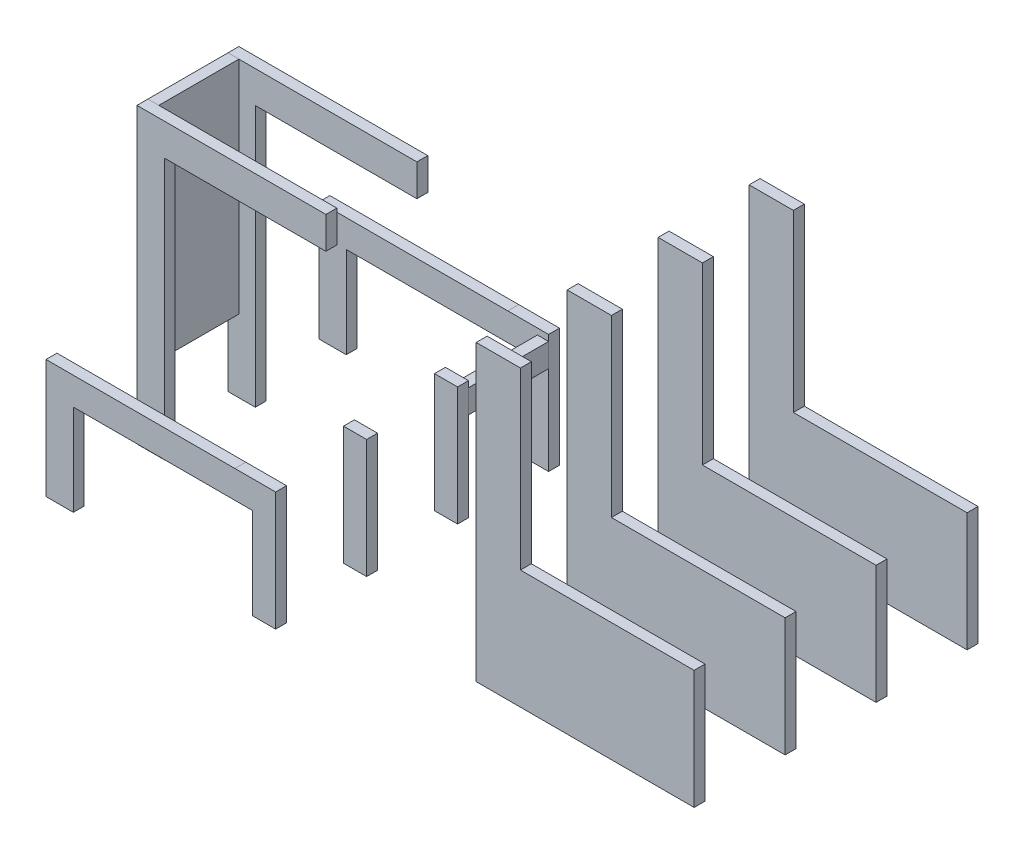
SolidWorks part; units mm, degrees
material "AISI 316 Stainless Steel Sheet (SS)"
ref_plane "Front Plane" through (0, 0, 0) normal (0, 0, 1) x (1, 0, 0)
ref_plane "Top Plane" through (0, 0, 0) normal (0, 1, 0) x (1, 0, 0)
ref_plane "Right Plane" through (0, 0, 0) normal (1, 0, 0) x (0, 0, -1)
sketch "Sketch1"
  dimension "D1" = 50
  dimension "D2" = 123.013
  dimension "D3" = 173.013
  dimension "D4" = 229.7747
  dimension "D5" = 171.9467
  dimension "D6" = 93.5182
  dimension "D7" = 166.8435
  dimension "D8" = 228.8836
  dimension "D9" = 229.7747
  dimension "D10" = 744.7238
  dimension "D11" = 447.3982
  dimension "D12" = 748.8136
  dimension "D13" = 598.8136
  dimension "D14" = 130
  dimension "D15" = 130
sketch_block_instance "Block1-1"
sketch_block "Block1" parameters "D1"=100, "D2"=20
sketch_block_instance "Block1-2"
sketch_block_instance "Block2-1"
sketch_block "Block2" parameters "D1"=50
sketch_block_instance "Block3-1"
sketch_block "Block3" parameters "D1"=150, "D2"=20
sketch_block_instance "Block3-2"
sketch_block_instance "Block4-1"
sketch_block "Block4" parameters "D2"=2.213, "D1"=50
sketch_block_instance "Block1-4"
sketch_block_instance "Block3-4"
sketch_block_instance "Block1-5"
sketch_block_instance "Block4-2"
sketch_block_instance "Block4-4"
sketch_block_instance "Block5-1"
sketch_block "Block5" parameters "D1"=200, "D2"=75, "D3"=75, "D4"=100
sketch_block_instance "Block5-2"
sketch_block_instance "Block2-2"
sketch_block_instance "Block3-8"
sketch "Sketch2" plane through (0, 0, 0) normal (0, 0, 1) x (1, 0, 0)
  line L0 (-466.6958, -172.0881) -> (-466.6958, -15.3598)
  line L1 (-244.3322, -302.6343) -> (-496.7215, -302.6343)
  line L2 (-244.3322, -302.6343) -> (-244.3322, -172.0881)
  line L3 (-244.3322, -172.0881) -> (-466.6958, -172.0881)
  line L4 (-496.7215, -302.6343) -> (-496.7215, 19.7481)
  line L5 (-466.6958, -15.3598) -> (-289.0913, -15.3598)
  line L6 (-289.0913, -15.3598) -> (-289.0913, 19.7481)
  line L7 (-289.0913, 19.7481) -> (-496.7215, 19.7481)
  line L8 (24.7298, -111.854) -> (215.6434, -111.854)
  line L9 (215.6434, -111.854) -> (215.6434, -242.4002)
  line L10 (215.6434, -242.4002) -> (-23.9267, -242.4002)
  line L11 (-23.9267, -242.4002) -> (-23.9267, 80.4875)
  line L12 (-23.9267, 80.4875) -> (24.7298, 80.4875)
  line L13 (24.7298, 80.4875) -> (24.7298, -111.854)
extrude "Boss-Extrude1" add sketch "Sketch2" along normal blind 12
pattern_linear "LPattern1" count 4 spacing 100 along (0, 0, 1) of bodies 102 101
sketch "Sketch3" plane through (0, 0, 112) normal (0, 0, 1) x (1, 0, 0)
  line L0 (-496.7215, -302.6343) -> (-244.3322, -302.6343) construction
  line L1 (-466.6958, -302.6343) -> (-269.725, -302.6343)
  line L2 (-466.6958, -302.6343) -> (-466.6958, -202.4226)
  line L3 (-466.6958, -202.4226) -> (-269.725, -202.4226)
  line L4 (-269.725, -302.6343) -> (-269.725, -202.4226)
  line L5 (-466.6958, -172.0881) -> (-466.6958, -15.3598) construction
  line L6 (-244.3322, -302.6343) -> (-244.3322, -172.0881) construction
  dimension "D1" = 25.3928
extrude "Cut-Extrude1" cut sketch "Sketch3" against normal through all both and the other way through all
sketch "Sketch4" plane through (-496.7215, 0, 0) normal (-1, 0, 0) x (0, 0, 1)
  line L25 (200, 19.7481) -> (200, -302.6343) construction
  line L26 (112, 19.7481) -> (200, 19.7481)
  line L27 (112, 19.7481) -> (112, -222.937)
  line L28 (112, -222.937) -> (200, -222.937)
  line L29 (200, 19.7481) -> (200, -222.937)
extrude "Boss-Extrude2" add sketch "Sketch4" against normal blind 12 separate body
sketch "Sketch5" plane through (0, 0, 12) normal (0, 0, 1) x (1, 0, 0)
  line L0 (-244.3322, -302.6343) -> (-244.3322, -172.0881) construction
  line L1 (-244.3322, -178.8069) -> (-256.5963, -178.8069)
  line L2 (-244.3322, -178.8069) -> (-244.3322, -204.6688)
  line L3 (-244.3322, -204.6688) -> (-256.5963, -204.6688)
  line L4 (-256.5963, -178.8069) -> (-256.5963, -204.6688)
extrude "Boss-Extrude3" add sketch "Sketch5" along normal up to surface (88 mm away) separate body up to face at (-372.2103, -162.5652, 100)
sketch "Sketch6" plane through (0, 0, 312) normal (0, 0, 1) x (1, 0, 0)
  line L1 (-289.0913, 19.7481) -> (-496.7215, 19.7481)
  line L2 (-289.0913, 19.7481) -> (-289.0913, -172.1101)
  line L3 (-289.0913, -172.1101) -> (-496.7215, -172.1101)
  line L4 (-496.7215, 19.7481) -> (-496.7215, -172.1101)
extrude "Cut-Extrude2" cut sketch "Sketch6" against normal through all
sketch "Sketch7" plane through (0, 0, 212) normal (0, 0, 1) x (1, 0, 0)
  line L1 (-466.6958, -172.0881) -> (-269.725, -172.0881)
  line L2 (-466.6958, -172.0881) -> (-466.6958, -202.4226)
  line L3 (-466.6958, -202.4226) -> (-269.725, -202.4226)
  line L4 (-269.725, -172.0881) -> (-269.725, -202.4226)
extrude "Cut-Extrude3" cut sketch "Sketch7" against normal blind 184
equation "\"D10@Sketch1\"=\"D8@Sketch1\"+3*\"D5@Sketch1\""
equation "\"D11@Sketch1\"=\"D7@Sketch1\"+3*\"D6@Sketch1\""
equation "\"D12@Sketch1\"=\"D4@Sketch1\"+3*\"D3@Sketch1\""
equation "\"D13@Sketch1\"=\"D9@Sketch1\"+3*\"D2@Sketch1\""
